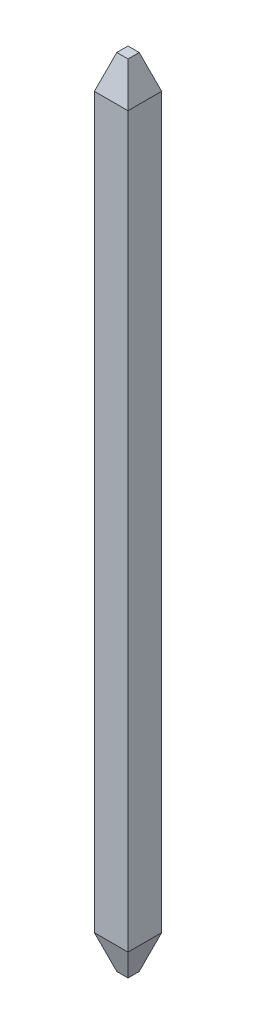
SolidWorks part; units mm, degrees
material "Nickel"
ref_plane "Ebene vorne" through (0, 0, 0) normal (0, 0, 1) x (1, 0, 0)
ref_plane "Ebene oben" through (0, 0, 0) normal (0, 1, 0) x (1, 0, 0)
ref_plane "Ebene rechts" through (0, 0, 0) normal (1, 0, 0) x (0, 0, -1)
sketch "Skizze1" plane through (0, 0, 0) normal (0, 1, 0) x (1, 0, 0)
  line L1 (-0.3, 0.3) -> (0.3, 0.3)
  line L2 (-0.3, 0.3) -> (-0.3, -0.3)
  line L3 (-0.3, -0.3) -> (0.3, -0.3)
  line L4 (0.3, 0.3) -> (0.3, -0.3)
  line L5 (-0.3, 0.3) -> (0.3, -0.3) construction
  line L6 (-0.3, -0.3) -> (0.3, 0.3) construction
  point P0 (0, 0)
  dimension "D1" = 0.6
extrude "Aufsatz-Linear austragen1" add sketch "Skizze1" along normal blind 14.2
chamfer "Fase1" distance 0.6 distance2 0.2 4 edges at (-0.3, 14.2, 0) (0, 14.2, -0.3) (0.3, 14.2, 0) (0, 14.2, 0.3)
chamfer "Fase2" distance 0.2 distance2 0.6 4 edges at (0, 0, -0.3) (-0.3, 0, 0) (0, 0, 0.3) (0.3, 0, 0)
